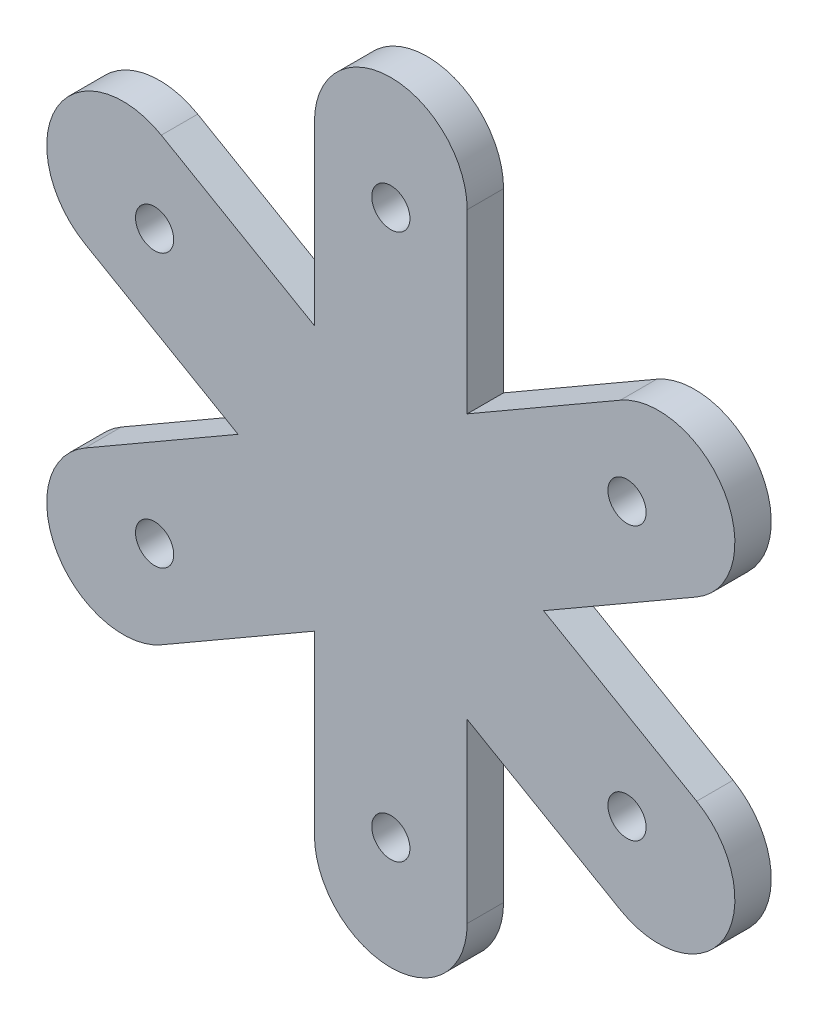
SolidWorks part; units mm, degrees
ref_plane "前视基准面" through (0, 0, 0) normal (0, 0, 1) x (1, 0, 0)
ref_plane "上视基准面" through (0, 0, 0) normal (0, 1, 0) x (1, 0, 0)
ref_plane "右视基准面" through (0, 0, 0) normal (1, 0, 0) x (0, 0, -1)
sketch "草图1" plane through (0, 0, 0) normal (0, 0, 1) x (1, 0, 0)
  line L0 (0, 0) -> (0, -85) construction
  line L1 (21, 0) -> (21, -48.6269)
  line L2 (-21, 0) -> (-21, -48.6269)
  line L3 (84.1122, -60.6865) -> (42, -85)
  line L4 (63.1122, -24.3135) -> (21, -48.6269)
  line L5 (63.1122, -145.6865) -> (21, -121.3731)
  line L6 (84.1122, -109.3135) -> (42, -85)
  line L7 (-21, -170) -> (-21, -121.3731)
  line L8 (21, -170) -> (21, -121.3731)
  line L9 (-84.1122, -109.3135) -> (-42, -85)
  line L10 (-63.1122, -145.6865) -> (-21, -121.3731)
  line L11 (-63.1122, -24.3135) -> (-21, -48.6269)
  line L12 (-84.1122, -60.6865) -> (-42, -85)
  arc A0 (21, 0) -> (-21, 0) centre (0, 0) ccw
  arc A3 (84.1122, -60.6865) -> (63.1122, -24.3135) centre (73.6122, -42.5) ccw
  arc A5 (63.1122, -145.6865) -> (84.1122, -109.3135) centre (73.6122, -127.5) ccw
  arc A7 (-21, -170) -> (21, -170) centre (0, -170) ccw
  arc A9 (-84.1122, -109.3135) -> (-63.1122, -145.6865) centre (-73.6122, -127.5) ccw
  arc A11 (-63.1122, -24.3135) -> (-84.1122, -60.6865) centre (-73.6122, -42.5) ccw
  circle A26 centre (0, -10) radius 5.25
  circle A27 centre (64.9519, -47.5) radius 5.25
  circle A28 centre (64.9519, -122.5) radius 5.25
  circle A29 centre (0, -160) radius 5.25
  circle A30 centre (-64.9519, -122.5) radius 5.25
  circle A31 centre (-64.9519, -47.5) radius 5.25
  point P3 (0, -42.5)
  point P37 (0, -85)
  point P43 (0, -85)
  dimension "D2" = 10.5
  dimension "D5" = 75
  dimension "D1" = 42
  dimension "D3" = 85
  dimension "D4" = 6
  dimension "D6" = 6
extrude "凸台-拉伸1" add sketch "草图1" along normal blind 10
